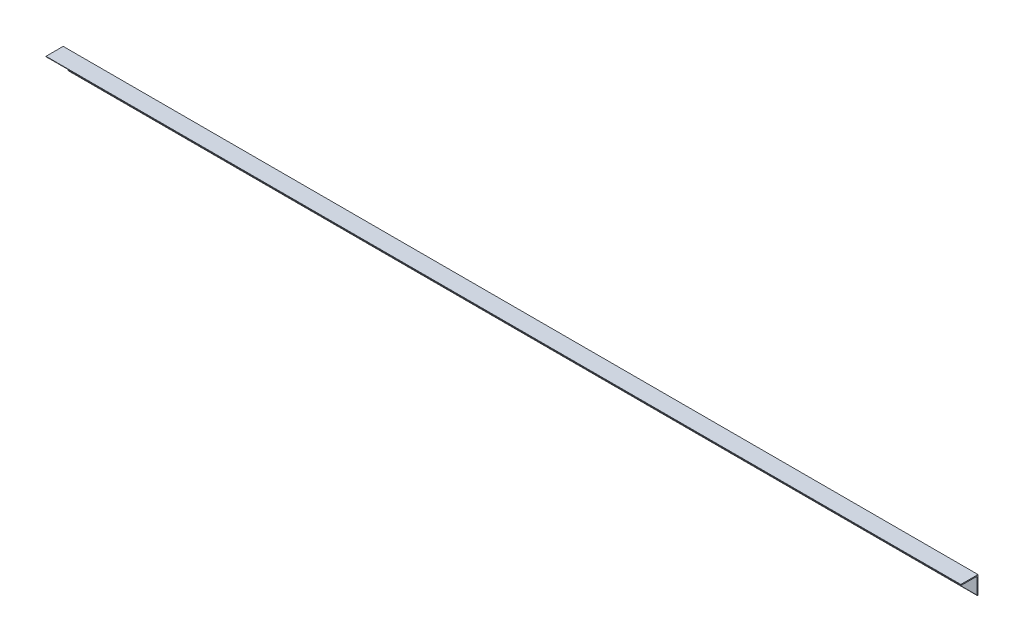
SolidWorks part; units mm, degrees
ref_plane "Front Plane" through (0, 0, 0) normal (0, 0, 1) x (1, 0, 0)
ref_plane "Top Plane" through (0, 0, 0) normal (0, 1, 0) x (1, 0, 0)
ref_plane "Right Plane" through (0, 0, 0) normal (1, 0, 0) x (0, 0, -1)
sketch "Sketch1" plane through (0, 0, 0) normal (0, 0, 1) x (1, 0, 0)
  line L0 (0, 0) -> (-4525, 0)
  dimension "D1" = 4525
other "Angle iron 35 X 35 X 5(2)"
ref_plane "Plane2" through (0, 0, 0) normal (-1, 0, 0) x (0, -1, 0)
sketch "Sketch13" plane through (0, 0, 0) normal (-1, 0, 0) x (0, -1, 0)
  line L0 (0, 0) -> (0, 85)
  line L1 (0, 42.5) -> (5, 42.5) construction
  line L2 (5, 80) -> (5, 10)
  line L3 (10, 5) -> (85, 5)
  line L4 (45, 5) -> (45, 0) construction
  line L5 (90, 0) -> (0, 0)
  arc A0 (90, 0) -> (85, 5) centre (85, 0) ccw
  arc A1 (0, 85) -> (5, 80) centre (0, 80) cw
  arc A2 (10, 5) -> (5, 10) centre (10, 10) cw
  point P10 (45, 0)
  point P14 (0, 42.5)
  point P15 (5, 42.5)
  point P16 (45, 5)
  point P17 (5, 85)
  point P18 (90, 5)
  point P21 (0, 0)
  dimension "D2" = 5
  dimension "D3" = 90
  dimension "Radius_1" = 5
  dimension "D1" = 5
  dimension "D4" = 85
sketch "Sketch14" plane through (0, 0, 5) normal (0, 0, 1) x (1, 0, 0)
  line L1 (-4525, -90) -> (0, -90) construction
  line L2 (0, -5) -> (-30, -5)
  line L3 (0, -5) -> (0, -90)
  line L4 (0, -90) -> (-30, -90)
  line L5 (-30, -5) -> (-30, -90)
  dimension "D1" = 30
extrude "Cut-Extrude1" [suppressed] cut sketch "Sketch14" against normal through all both and the other way through all
fillet "Fillet1" [suppressed] radius 5
sketch "Sketch15" plane through (0, 0, 5) normal (0, 0, 1) x (1, 0, 0)
  line L0 (-4525, -90) -> (0, -90) construction
  line L1 (-4525, -5) -> (-4495, -5)
  line L2 (-4525, -5) -> (-4525, -90)
  line L3 (-4525, -90) -> (-4495, -90)
  line L4 (-4495, -5) -> (-4495, -90)
  dimension "D1" = 30
extrude "Cut-Extrude2" cut sketch "Sketch15" against normal through all both and the other way through all
